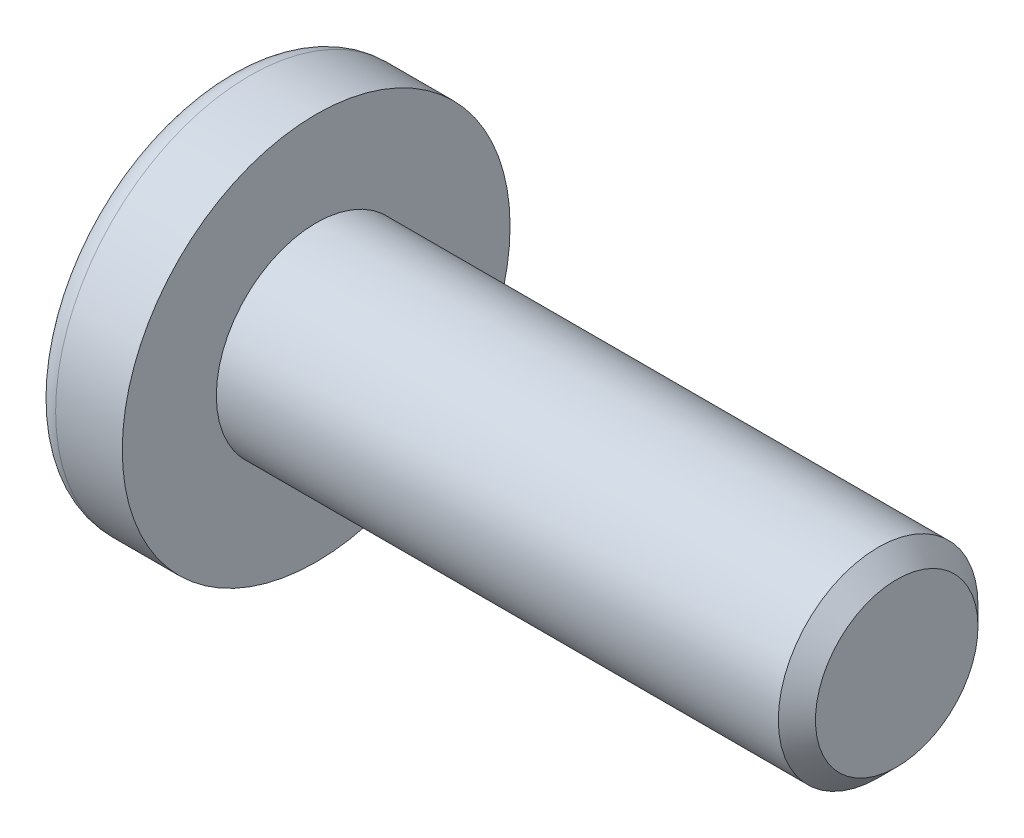
SolidWorks part; units mm, degrees
material "Alloy Steel"
ref_plane "Plane1" through (0, 0, 0) normal (0, 0, 1) x (1, 0, 0)
ref_plane "Plane2" through (0, 0, 0) normal (0, 1, 0) x (1, 0, 0)
ref_plane "Plane3" through (0, 0, 0) normal (1, 0, 0) x (0, 0, -1)
revolve "Base-Revolve" add sketch "BodySke" angle 360 about L2
sketch "BodySke" plane through (0, 0, 0) normal (0, 0, 1) x (1, 0, 0)
  line L0 (1.5748, 1.0922) -> (1.5748, 2.1209)
  line L1 (1.8021, 6.35) -> (1.8021, -3.175) construction
  line L2 (-25.4, 0) -> (127, 0) construction
  line L3 (7.9248, 0) -> (0, 0)
  line L4 (1.5748, 1.0922) -> (7.9248, 1.0922)
  line L5 (7.9248, 1.0922) -> (7.9248, 0)
  line L6 (0.8457, 2.1209) -> (1.5748, 2.1209)
  line L7 (1.5748, -1.0922) -> (7.9248, -1.0922) construction
  line L8 (1.5748, 6.35) -> (1.5748, -3.175) construction
  arc A0 (0.6381, 2.0132) -> (0, 0) centre (3.495, 0) ccw
  arc A2 (0.6381, 2.0132) -> (0.8457, 2.1209) centre (0.8457, 1.8669) cw
  dimension "Head_fillet_rad" = 0.254
  dimension "Head_crown_rad" = 3.495
  dimension "Head_ht" = 1.5748
  dimension "Diameter" = 2.1844
  dimension "Length" = 6.35
  dimension "Head_dia" = 4.2418
  dimension "Advance" = 0.4547
  dimension "Thread_nom" = 6.35
cosmetic thread "ThreadCosmetic" parameters "Thread_length"=5.8953, "Thread_minor"=1.6459
sketch "Sketch3" plane through (0, 0, 0) normal (1, 0, 0) x (0, 0, -1)
  line L0 (0.3429, -1.3843) -> (-0.3429, -1.3843)
  line L1 (0.3429, -1.3843) -> (0.3429, 1.3843)
  line L2 (-0.3429, 1.3843) -> (0.3429, 1.3843)
  line L3 (-0.3429, 1.3843) -> (-0.3429, -1.3843)
  dimension "D1" = 1.3843
  dimension "Cross_dia" = 2.7686
  dimension "D2" = 0.3429
  dimension "Cross_width" = 0.6858
ref_plane "Plane4" through (1.4986, 0, 0) normal (1, 0, 0) x (0, 0, -1)
sketch "Sketch4" plane through (1.4986, 0, 0) normal (1, 0, 0) x (0, 0, -1)
  line L0 (0.1714, -0.1715) -> (-0.1714, -0.1715)
  line L1 (0.1714, -0.1715) -> (0.1714, 0.1714)
  line L2 (-0.1714, 0.1714) -> (0.1714, 0.1714)
  line L3 (-0.1714, 0.1714) -> (-0.1714, -0.1715)
  dimension "D1" = 0.3429
  dimension "D2" = 0.3429
  dimension "D3" = 0.1714
  dimension "D4" = 0.1714
loft "Cut-Loft1" cut profiles "Sketch3", "Sketch4"
pattern_circular "CirPattern1" count 2 every 90 about axis through (0, 0, 0) along (1, 0, 0) of "Cut-Loft1"
chamfer "Chamfer1" distance 0.2032 angle 45 1 edges at (7.9248, 0, 1.0922)
equation "\"D1@Sketch3\" = \"Cross_dia@Sketch3\" / 2"
equation "\"D2@Sketch3\" = \"Cross_width@Sketch3\" / 2"
equation "\"D1@Sketch4\" = \"Cross_width@Sketch3\" *.5"
equation "\"D2@Sketch4\" = \"D1@Sketch4\""
equation "\"D3@Sketch4\" = \"D1@Sketch4\" / 2"
equation "\"D4@Sketch4\" = \"D2@Sketch4\" / 2"
equation "\"Thread_length@ThreadCosmetic\" = ((sgn( (\"Length@BodySke\" - \"Advance@BodySke\" ) - \"Thread_nom@BodySke\" )-1)*( (\"Length@BodySke\" - \"Advance@BodySke\" ) - \"Thread_nom@BodySke\" ))/-2+ \"Thread_nom@BodySke\""
